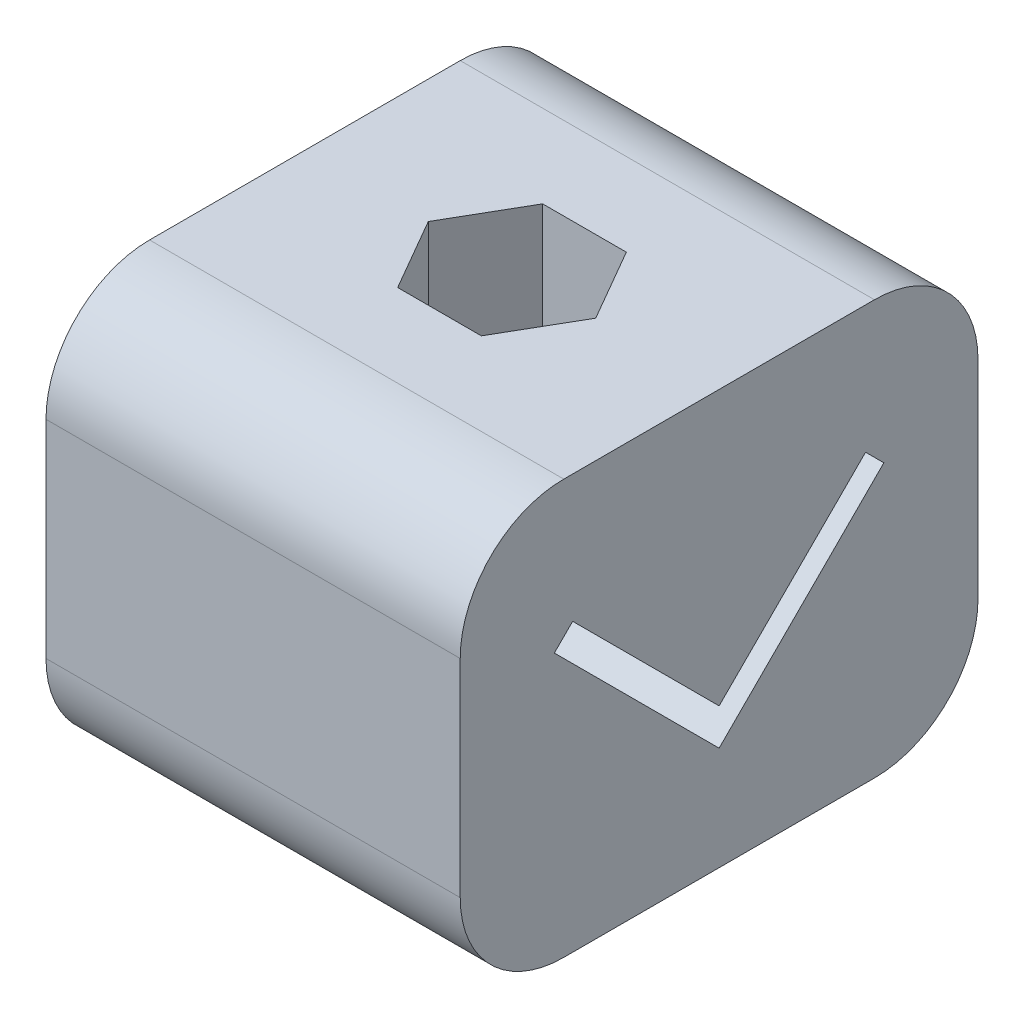
SolidWorks part; units mm, degrees
material "ABS"
ref_plane "Front Plane" through (0, 0, 0) normal (0, 0, 1) x (1, 0, 0)
ref_plane "Top Plane" through (0, 0, 0) normal (0, 1, 0) x (1, 0, 0)
ref_plane "Right Plane" through (0, 0, 0) normal (1, 0, 0) x (0, 0, -1)
sketch "Sketch1" plane through (0, 0, 0) normal (0, 0, 1) x (1, 0, 0)
  line L0 (0, 0) -> (12.7, 0)
  line L1 (12.7, 0) -> (12.7, 25.4)
  line L2 (12.7, 25.4) -> (-12.7, 25.4)
  line L3 (-12.7, 25.4) -> (-12.7, 0)
  line L4 (-12.7, 0) -> (0, 0)
  dimension "D1" = 25.4
  dimension "D2" = 25.4
extrude "Boss-Extrude1" add sketch "Sketch1" along normal mid plane 31.75
sketch "Sketch2" plane through (-12.7, 0, 0) normal (-1, 0, 0) x (0, 0, 1)
  line L0 (0, 8.5951) -> (-8.9803, 17.5753)
  line L1 (-8.9803, 17.5753) -> (-10.1028, 16.4528)
  line L2 (-10.1028, 16.4528) -> (0, 6.35)
  line L3 (0, 6.35) -> (10.1028, 16.4528)
  line L4 (10.1028, 16.4528) -> (8.9803, 17.5753)
  line L5 (8.9803, 17.5753) -> (0, 8.5951)
  line L6 (-11.3146, 0) -> (21.0706, 0) construction
  line L7 (-15.875, 25.4) -> (-15.875, 0) construction
  line L8 (-10.1028, 16.4528) -> (-15.875, 16.4528) construction
  line L9 (10.1028, 16.4528) -> (15.875, 16.4528) construction
  line L10 (15.875, 25.4) -> (15.875, 0) construction
  dimension "D1" = 1.5875
  dimension "D2" = 6.35
  dimension "D3" = 12.7
extrude "Cut-Extrude1" cut sketch "Sketch2" against normal blind 152.4
hole_wizard "1/4 (0.25) Diameter Hole1" positions "Sketch5" profile "Sketch6" hole size "1/4" standard "ANSI Inch" end condition through all
sketch "Sketch5" plane through (0, 25.4, 0) normal (0, 1, 0) x (1, 0, 0)
  line L0 (-12.7, -15.875) -> (-12.7, 15.875) construction
  point P0 (0, 0)
  point P2 (76.2, 0)
  dimension "D1" = 12.7
  dimension "D2" = 76.2
sketch "Sketch6" plane through (0, 25.4, 0) normal (1, 0, 0) x (0, 0, 1)
  line L0 (0, 0) -> (0, 25.4)
  line L1 (0, 25.4) -> (1.9844, 25.4)
  line L2 (1.9844, 25.4) -> (1.9844, 0)
  line L5 (1.9844, 0) -> (0, 0)
  line L11 (0, -6.35) -> (0, 107.95) construction
  dimension "Thru Hole Dia." = 3.9688
  dimension "Thru Hole Depth" = 25.4
sketch "Sketch7" plane through (0, 25.4, 0) normal (0, 1, 0) x (1, 0, 0)
  line L1 (5.1326, 0) -> (2.5663, 4.445)
  line L2 (2.5663, 4.445) -> (-2.5663, 4.445)
  line L3 (-2.5663, 4.445) -> (-5.1326, 0)
  line L4 (-5.1326, 0) -> (-2.5663, -4.445)
  line L5 (-2.5663, -4.445) -> (2.5663, -4.445)
  line L6 (2.5663, -4.445) -> (5.1326, 0)
  circle A0 centre (0, 0) radius 4.445 construction
  dimension "D1" = 8.89
extrude "Cut-Extrude2" cut sketch "Sketch7" against normal blind 11.43
sketch "Sketch8" plane through (0, 0, 0) normal (0, -1, 0) x (1, 0, 0)
  circle A0 centre (0, 0) radius 4.1275
  dimension "D1" = 8.255
extrude "Cut-Extrude3" cut sketch "Sketch8" against normal blind 5.08
fillet "Fillet1" radius 6.35 4 edges at (0, 0, 15.875) (0, 0, -15.875) (0, 25.4, -15.875) (0, 25.4, 15.875)
